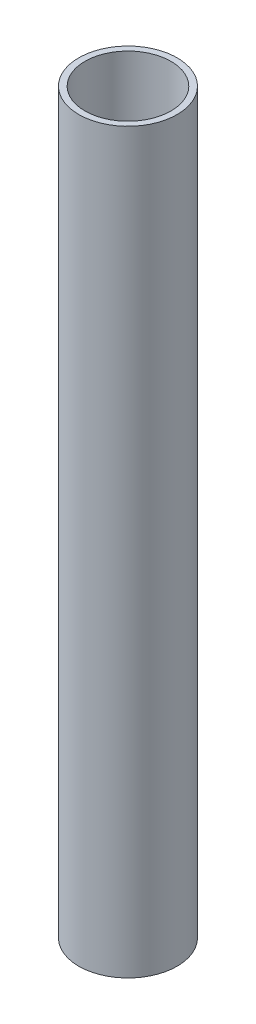
SolidWorks part; units mm, degrees
ref_plane "Front Plane" through (0, 0, 0) normal (0, 0, 1) x (1, 0, 0)
ref_plane "Top Plane" through (0, 0, 0) normal (0, 1, 0) x (1, 0, 0)
ref_plane "Right Plane" through (0, 0, 0) normal (1, 0, 0) x (0, 0, -1)
sketch "Sketch1" plane through (0, 0, 0) normal (0, 1, 0) x (1, 0, 0)
  circle A0 centre (0, 0) radius 4
  circle A1 centre (0, 0) radius 3.5
extrude "Boss-Extrude1" add sketch "Sketch1" along normal blind 60
